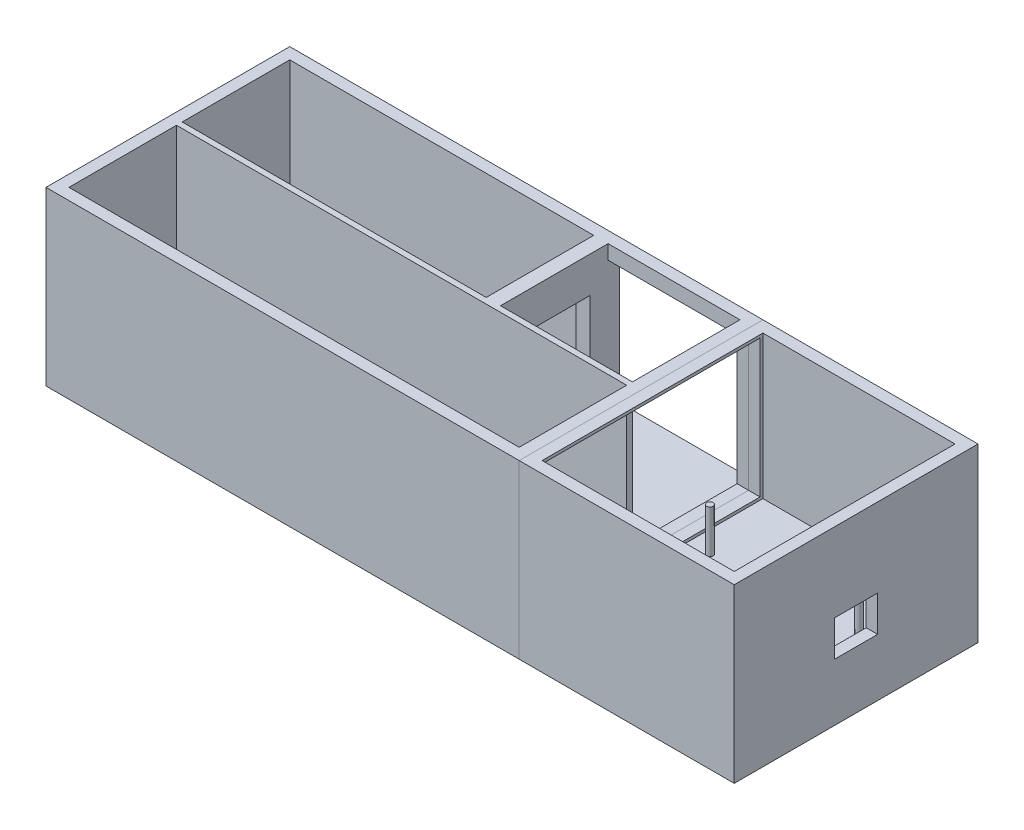
SolidWorks part; units mm, degrees
material "ABS"
ref_plane "Ön Düzlem" through (0, 0, 0) normal (0, 0, 1) x (1, 0, 0)
ref_plane "Üst Düzlem" through (0, 0, 0) normal (0, 1, 0) x (1, 0, 0)
ref_plane "Sağ Düzlem" through (0, 0, 0) normal (1, 0, 0) x (0, 0, -1)
sketch "Çizim1" plane through (0, 0, 0) normal (0, 1, 0) x (1, 0, 0)
  line L1 (0, 0) -> (75, 0)
  line L2 (0, 0) -> (0, 85)
  line L3 (0, 85) -> (75, 85)
  line L4 (75, 0) -> (75, 85)
  dimension "D1" = 75
  dimension "D2" = 85
extrude "Yükseklik-Ekstrüzyon1" add sketch "Çizim1" along normal blind 60
sketch "Çizim3" plane through (0, 60, 0) normal (0, 1, 0) x (1, 0, 0)
  line L0 (0, 85) -> (0, 0) construction
  line L1 (4, 81) -> (71, 81)
  line L2 (4, 81) -> (4, 4)
  line L3 (4, 4) -> (71, 4)
  line L4 (71, 81) -> (71, 4)
  line L5 (75, 85) -> (0, 85) construction
  line L6 (0, 0) -> (75, 0) construction
  line L7 (75, 0) -> (75, 85) construction
  dimension "D1" = 4
  dimension "D2" = 4
  dimension "D3" = 4
  dimension "D4" = 4
extrude "Kes-Ekstrüzyon1" cut sketch "Çizim3" against normal blind 50
sketch "Çizim4" plane through (0, 0, 0) normal (-1, 0, 0) x (0, 0, 1)
  line L1 (-85, 60) -> (0, 60)
  line L2 (-85, 60) -> (-85, 0)
  line L3 (-85, 0) -> (0, 0)
  line L4 (0, 60) -> (0, 0)
extrude "Yükseklik-Ekstrüzyon2" add sketch "Çizim4" along normal blind 165 separate body
sketch "Çizim5" plane through (0, 60, 0) normal (0, 1, 0) x (1, 0, 0)
  line L0 (-165, 0) -> (-165, 85) construction
  line L1 (-161, 81) -> (-4, 81)
  line L2 (-161, 81) -> (-161, 4)
  line L3 (-161, 4) -> (-4, 4)
  line L4 (-4, 81) -> (-4, 4)
  line L5 (-165, 0) -> (0, 0) construction
  line L6 (-165, 85) -> (0, 85) construction
  line L7 (0, 0) -> (0, 85) construction
  dimension "D1" = 4
  dimension "D2" = 4
  dimension "D3" = 4
  dimension "D4" = 4
extrude "Kes-Ekstrüzyon2" cut sketch "Çizim5" against normal blind 50
sketch "Çizim6" plane through (0, 10, 0) normal (0, 1, 0) x (1, 0, 0)
  line L0 (71, 81) -> (4, 81) construction
  line L1 (10, 56.5) -> (65, 56.5) construction
  line L2 (10, 56.5) -> (10, 28.5) construction
  line L3 (10, 28.5) -> (65, 28.5) construction
  line L4 (65, 56.5) -> (65, 28.5) construction
  line L5 (71, 4) -> (71, 81) construction
  circle A0 centre (11.5, 55) radius 1.13 construction
  circle A1 centre (63.5, 55) radius 1.13 construction
  circle A2 centre (63.5, 30) radius 1.13 construction
  circle A3 centre (11.5, 30) radius 1.13 construction
  point P6 (37.5, 81)
  point P7 (37.5, 56.5)
  point P10 (71, 42.5)
  point P11 (65, 42.5)
  dimension "D3" = 2.26
  dimension "D1" = 55
  dimension "D2" = 28
  dimension "D4" = 1.5
  dimension "D5" = 1.5
  dimension "D8" = 1.5
  dimension "D9" = 1.5
  dimension "D10" = 1.5
  dimension "D6" = 2
  dimension "D7" = 2
sketch "Çizim7" plane through (75, 0, 0) normal (1, 0, 0) x (0, 0, -1)
  line L0 (0, 60) -> (0, 0) construction
  line L1 (35, 32.5) -> (50, 32.5)
  line L2 (35, 32.5) -> (35, 20)
  line L3 (35, 20) -> (50, 20)
  line L4 (50, 32.5) -> (50, 20)
  line L6 (0, 0) -> (85, 0) construction
  dimension "D1" = 12.5
  dimension "D2" = 15
  dimension "D3" = 35
  dimension "D4" = 20
extrude "Kes-Ekstrüzyon4" cut sketch "Çizim7" against normal up to next (4 mm away)
sketch "Çizim8" plane through (4, 0, 0) normal (1, 0, 0) x (0, 0, -1)
  line L0 (0, 60) -> (0, 0) construction
  line L1 (5, 59) -> (80, 59)
  line L2 (5, 59) -> (5, 11)
  line L3 (5, 11) -> (80, 11)
  line L4 (80, 59) -> (80, 11)
  line L5 (0, 60) -> (85, 60) construction
  dimension "D1" = 48
  dimension "D2" = 75
  dimension "D3" = 5
  dimension "D4" = 1
extrude "Kes-Ekstrüzyon5" cut sketch "Çizim8" against normal blind 10
sketch "Çizim9" plane through (-161, 0, 0) normal (1, 0, 0) x (0, 0, -1)
  line L0 (0, 60) -> (85, 60) construction
  line L1 (41.5, 60) -> (43.5, 60)
  line L2 (41.5, 60) -> (41.5, 10)
  line L3 (41.5, 10) -> (43.5, 10)
  line L4 (43.5, 60) -> (43.5, 10)
  line L5 (56.5, 10) -> (28.5, 10) construction
  line L6 (0, 60) -> (0, 0) construction
  dimension "D1" = 2
  dimension "D2" = 41.5
extrude "Yükseklik-Ekstrüzyon3" add sketch "Çizim9" along normal up to surface (157 mm away) up to face at (-4, 35, -42.5)
sketch "Çizim11" plane through (0, 10, 0) normal (0, 1, 0) x (1, 0, 0)
  circle A0 centre (11.5, 55) radius 1.13
  circle A1 centre (63.5, 55) radius 1.13
  circle A2 centre (63.5, 30) radius 1.13
  circle A3 centre (11.5, 30) radius 1.13
  dimension "D1" = 2.26
extrude "Kes-Ekstrüzyon6" cut sketch "Çizim11" against normal blind 1
sketch "Çizim12" plane through (0, 9, 0) normal (0, 1, 0) x (1, 0, 0)
  circle A0 centre (11.5, 55) radius 1.13
  circle A1 centre (63.5, 55) radius 1.13
  circle A2 centre (63.5, 30) radius 1.13
  circle A3 centre (11.5, 30) radius 1.13
  dimension "D1" = 2.26
extrude "Yükseklik-Ekstrüzyon4" add sketch "Çizim12" along normal blind 16
sketch "Çizim13" plane through (0, 0, -85) normal (0, 0, -1) x (-1, 0, 0)
  line L0 (165, 0) -> (0, 0) construction
  line L1 (5, 55) -> (50, 55)
  line L2 (5, 55) -> (5, 10)
  line L3 (5, 10) -> (50, 10)
  line L4 (50, 55) -> (50, 10)
  line L5 (0, 60) -> (0, 0) construction
  dimension "D1" = 45
  dimension "D2" = 10
  dimension "D3" = 5
  dimension "D4" = 45
extrude "Kes-Ekstrüzyon7" cut sketch "Çizim13" against normal up to next (4 mm away)
sketch "Çizim14" plane through (0, 0, -81) normal (0, 0, 1) x (1, 0, 0)
  line L0 (-165, 60) -> (0, 60) construction
  line L1 (-55, 60) -> (-50, 60)
  line L2 (-55, 60) -> (-55, 10)
  line L3 (-55, 10) -> (-50, 10)
  line L4 (-50, 60) -> (-50, 10)
  line L5 (-50, 10) -> (-161, 10) construction
  point P8 (0, 0)
  point P11 (0, 0)
  dimension "D1" = 5
extrude "Yükseklik-Ekstrüzyon5" add sketch "Çizim14" along normal up to next
sketch "Çizim15" plane through (-50, 0, 0) normal (1, 0, 0) x (0, 0, -1)
  line L0 (43.5, 10) -> (43.5, 60) construction
  line L1 (49.75, 47.5) -> (74.75, 47.5)
  line L2 (49.75, 47.5) -> (49.75, 22.5)
  line L3 (49.75, 22.5) -> (74.75, 22.5)
  line L4 (74.75, 47.5) -> (74.75, 22.5)
  line L5 (43.5, 60) -> (81, 60) construction
  point P6 (43.5, 35)
  point P7 (49.75, 35)
  point P10 (62.25, 60)
  point P11 (62.25, 47.5)
  dimension "D1" = 25
extrude "Kes-Ekstrüzyon8" cut sketch "Çizim15" against normal up to next (5 mm away)
